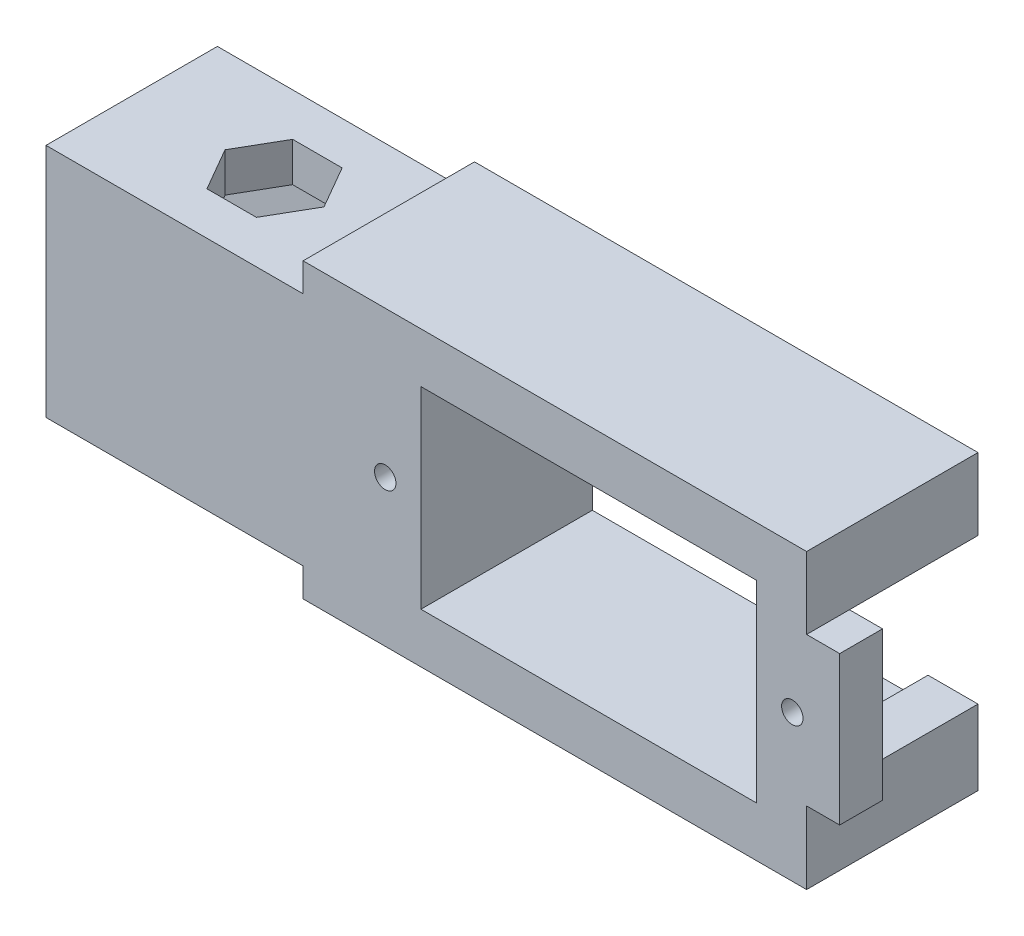
SolidWorks part; units mm, degrees
ref_plane "前视基准面" through (0, 0, 0) normal (0, 0, 1) x (1, 0, 0)
ref_plane "上视基准面" through (0, 0, 0) normal (0, 1, 0) x (1, 0, 0)
ref_plane "右视基准面" through (0, 0, 0) normal (1, 0, 0) x (0, 0, -1)
sketch "草图2" plane through (0, 0, 0) normal (0, 0, 1) x (1, 0, 0)
  line L0 (-15.25, 10.25) -> (15.25, 10.25)
  line L1 (-11.25, 6.25) -> (11.25, 6.25)
  line L2 (-11.25, 6.25) -> (-11.25, -6.25)
  line L3 (-11.25, -6.25) -> (11.25, -6.25)
  line L4 (11.25, 6.25) -> (11.25, -6.25)
  line L5 (-11.25, 6.25) -> (11.25, -6.25) construction
  line L6 (-11.25, -6.25) -> (11.25, 6.25) construction
  line L11 (-10.2, 6.25) -> (10.2, -6.25) construction
  line L12 (-10.2, -6.25) -> (10.2, 6.25) construction
  line L13 (15.25, 10.25) -> (15.25, -10.25)
  line L14 (-15.25, -10.25) -> (15.25, -10.25)
  line L15 (-15.25, 10.25) -> (-15.25, -10.25)
  point P0 (0, 0)
  point P5 (0, 0)
  dimension "D1" = 12.5
  dimension "D2" = 22.5
  dimension "D3" = 4
extrude "凸台-拉伸1" add sketch "草图2" along normal blind 12
sketch "草图3" plane through (0, 0, 12) normal (0, 0, 1) x (1, 0, 0)
  line L0 (0, 0) -> (0, 5) construction
  line L1 (-15.25, 5) -> (-18, 5)
  line L2 (-15.25, 10.25) -> (-15.25, -10.25) construction
  line L3 (-18, 5) -> (-18, -5)
  line L4 (-18, -5) -> (-15.25, -5)
  line L5 (-15.25, -5) -> (-15.25, 5)
  point P8 (-15.25, 0)
  point P10 (-16.625, -5)
  dimension "D1" = 36
  dimension "D2" = 10
extrude "凸台-拉伸2" add sketch "草图3" against normal blind 3
mirror "镜向1" about plane through (0, 0, 0) normal (1, 0, 0) of "凸台-拉伸2"
sketch "草图4" plane through (0, 0, 0) normal (0, 0, -1) x (-1, 0, 0)
  line L0 (0, 0) -> (8.8535, 0) construction
  line L1 (12.75, -5) -> (17.6907, -5)
  line L2 (12.75, -5) -> (12.75, 5)
  line L3 (12.75, 5) -> (17.6907, 5)
  line L4 (17.6907, -5) -> (17.6907, 5)
  line L5 (11.25, 6.25) -> (11.25, -6.25) construction
  dimension "D1" = 10
  dimension "D2" = 1.5
extrude "切除-拉伸1" cut sketch "草图4" against normal up to surface (9 mm away) up to face at (-16.625, 0, 9)
mirror "镜向2" about plane through (0, 0, 0) normal (1, 0, 0) of "切除-拉伸1"
sketch "草图5" plane through (-18, 0, 0) normal (-1, 0, 0) x (0, 0, 1)
  line L0 (12, 10.25) -> (12, 5) construction
  line L1 (12, 5) -> (12, -5) construction
  line L2 (12, -5) -> (12, -10.25) construction
  line L3 (12, -10.25) -> (0, -10.25) construction
  line L4 (0, -5) -> (0, -10.25) construction
  line L5 (0, 5) -> (0, -5) construction
  line L6 (0, 10.25) -> (0, 5) construction
  line L7 (12, 10.25) -> (0, 10.25) construction
  line L8 (12, 10.25) -> (12, 5)
  line L9 (12, 5) -> (12, -5)
  line L10 (12, -5) -> (12, -10.25)
  line L11 (12, -10.25) -> (0, -10.25)
  line L12 (0, -5) -> (0, -10.25)
  line L13 (0, 5) -> (0, -5)
  line L14 (0, 10.25) -> (0, 5)
  line L15 (12, 10.25) -> (0, 10.25)
extrude "凸台-拉伸3" add sketch "草图5" along normal blind 20
sketch "草图6" plane through (-15.25, 0, 0) normal (-1, 0, 0) x (0, 0, 1)
  line L5 (12, -5) -> (9, -5)
  line L6 (9, -5) -> (0, -5)
  line L7 (0, -5) -> (0, -10.25)
  line L8 (0, -10.25) -> (12, -10.25)
  line L9 (12, -10.25) -> (12, -5)
  line L10 (12, -5) -> (9, -5)
  line L11 (9, -5) -> (0, -5)
  line L12 (0, -5) -> (0, -10.25)
  line L13 (0, -10.25) -> (12, -10.25)
  line L14 (12, -10.25) -> (12, -5)
  dimension "D1" = 0
extrude "凸台-拉伸4" add sketch "草图6" along normal up to next
mirror "镜向3" about plane through (0, 0, 0) normal (0, 1, 0) of "凸台-拉伸4"
sketch "草图7" plane through (0, 0, 9) normal (0, 0, -1) x (-1, 0, 0)
  line L0 (11.25, 6.25) -> (11.25, -6.25) construction
  line L1 (-1.4179, 0) -> (17.5621, 0) construction
  circle A0 centre (14.25, 0) radius 0.75
  dimension "D1" = 3
  dimension "D2" = 1.5
extrude "切除-拉伸2" cut sketch "草图7" against normal through all
sketch "草图8" plane through (-38, 0, 0) normal (-1, 0, 0) x (0, 0, 1)
  line L0 (6, 10.25) -> (6, 4.7611) construction
  line L1 (1, -5) -> (11, -5)
  line L2 (1, -5) -> (1, 5)
  line L3 (1, 5) -> (11, 5)
  line L4 (11, -5) -> (11, 5)
  line L5 (12, 10.25) -> (0, 10.25) construction
  line L6 (0, 0) -> (4.6816, 0) construction
  dimension "D1" = 10
  dimension "D2" = 10
extrude "切除-拉伸3" cut sketch "草图8" against normal blind 18
sketch "草图10" plane through (0, 0, 0) normal (0, 0, -1) x (-1, 0, 0)
  line L0 (-15.25, 10.25) -> (38, 10.25) construction
  line L1 (20, 8.25) -> (43.1061, 8.25)
  line L2 (20, 8.25) -> (20, 16.0046)
  line L3 (20, 16.0046) -> (43.1061, 16.0046)
  line L4 (43.1061, 8.25) -> (43.1061, 16.0046)
  line L5 (38, 10.25) -> (38, -10.25) construction
  dimension "D1" = 2
  dimension "D2" = 18
extrude "切除-拉伸4" cut sketch "草图10" against normal through all
mirror "镜向4" about plane through (0, 0, 0) normal (0, 1, 0) of "切除-拉伸4"
sketch "草图11" plane through (0, -8.25, 0) normal (0, -1, 0) x (1, 0, 0)
  line L0 (-38, 6) -> (-41.4159, 6) construction
  line L2 (-29.5, 6) -> (-24.3196, 6) construction
  line L3 (-20, 12) -> (-20, 0) construction
  line L4 (-38, 0) -> (-38, 12) construction
  circle A1 centre (-28, 6) radius 1.5
  dimension "D1" = 3
  dimension "D3" = 8
extrude "切除-拉伸5" cut sketch "草图11" against normal through all
mirror "镜向5" about plane through (0, 0, 0) normal (1, 0, 0) of "切除-拉伸2"
sketch "草图12" plane through (-38, 0, 0) normal (-1, 0, 0) x (0, 0, 1)
  line L0 (11, 5) -> (1, 5) construction
  line L1 (0.5, -5.5) -> (11.5, -5.5)
  line L2 (0.5, -5.5) -> (0.5, 5.5)
  line L3 (0.5, 5.5) -> (11.5, 5.5)
  line L4 (11.5, -5.5) -> (11.5, 5.5)
  line L5 (11, -5) -> (11, 5) construction
  line L6 (1, 5) -> (1, -5) construction
  line L7 (1, -5) -> (11, -5) construction
  dimension "D1" = 0.5
  dimension "D2" = 0.5
  dimension "D3" = 0.5
  dimension "D4" = 0.5
extrude "切除-拉伸6" cut sketch "草图12" against normal up to surface (18 mm away) up to face at (-20, 0, 6)
sketch "草图13" plane through (0, 0, 12) normal (0, 0, 1) x (1, 0, 0)
  line L0 (11.25, 6.25) -> (-11.25, 6.25) construction
  line L1 (-11.75, -6.75) -> (11.75, -6.75)
  line L2 (-11.75, -6.75) -> (-11.75, 6.75)
  line L3 (-11.75, 6.75) -> (11.75, 6.75)
  line L4 (11.75, -6.75) -> (11.75, 6.75)
  line L5 (-11.75, -6.75) -> (11.75, 6.75) construction
  line L6 (-11.75, 6.75) -> (11.75, -6.75) construction
  line L7 (11.25, -6.25) -> (11.25, 6.25) construction
  point P0 (0, 0)
  dimension "D1" = 0.5
  dimension "D2" = 0.5
extrude "切除-拉伸7" cut sketch "草图13" against normal through all
sketch "草图14" plane through (0, 0, 12) normal (0, 0, 1) x (1, 0, 0)
  line L1 (18, -5) -> (8.8706, -5)
  line L2 (18, -5) -> (18, 5.2189)
  line L3 (18, 5.2189) -> (8.8706, 5.2189)
  line L4 (8.8706, -5) -> (8.8706, 5.2189)
extrude "切除-拉伸8" cut sketch "草图14" against normal through all
sketch "草图15" plane through (0, 8.25, 0) normal (0, 1, 0) x (1, 0, 0)
  line L0 (-20, 0) -> (-20, -12) construction
  line L1 (-24.5359, -6) -> (-26.2679, -3)
  line L2 (-26.2679, -3) -> (-29.7321, -3)
  line L3 (-29.7321, -3) -> (-31.4641, -6)
  line L4 (-31.4641, -6) -> (-29.7321, -9)
  line L5 (-29.7321, -9) -> (-26.2679, -9)
  line L6 (-26.2679, -9) -> (-24.5359, -6)
  circle A0 centre (-28, -6) radius 3 construction
  point P1 (-25.4019, -4.5)
  dimension "D1" = 6
extrude "切除-拉伸9" cut sketch "草图15" against normal up to next
sketch "草图16" plane through (0, 0, 0) normal (0, 0, -1) x (-1, 0, 0)
  line L0 (38, 8.25) -> (38, -8.25) construction
  line L1 (38, 0) -> (33.6818, 0) construction
  circle A0 centre (28, 0) radius 1.5
  dimension "D1" = 3
  dimension "D2" = 10
extrude "切除-拉伸10" cut sketch "草图16" against normal up to next
sketch "草图17" plane through (0, 0, 12) normal (0, 0, 1) x (1, 0, 0)
  line L1 (11.75, 5.2189) -> (17.567, 5.2189)
  line L2 (11.75, 5.2189) -> (11.75, -5.1761)
  line L3 (11.75, -5.1761) -> (17.567, -5.1761)
  line L4 (17.567, 5.2189) -> (17.567, -5.1761)
extrude "凸台-拉伸5" add sketch "草图17" against normal blind 3
ref_plane "基准面1" through (0, 0, 0) normal (-1, 0, 0) x (0, 0, 1)
mirror "镜向6" about plane through (0, 0, 0) normal (-1, 0, 0) of "切除-拉伸2"
